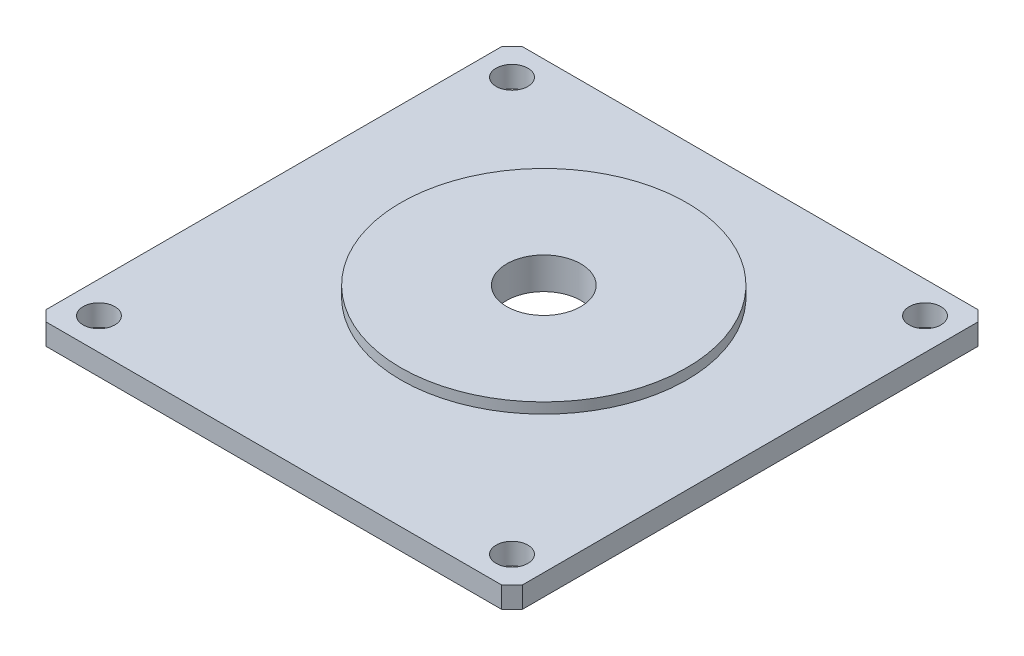
SolidWorks part; units mm, degrees
ref_plane "前视基准面" through (0, 0, 0) normal (0, 0, 1) x (1, 0, 0)
ref_plane "上视基准面" through (0, 0, 0) normal (0, 1, 0) x (1, 0, 0)
ref_plane "右视基准面" through (0, 0, 0) normal (1, 0, 0) x (0, 0, -1)
sketch "草图1" plane through (0, 0, 0) normal (0, 1, 0) x (1, 0, 0)
  line L1 (-22.5, -22.5) -> (22.5, -22.5)
  line L2 (-22.5, -22.5) -> (-22.5, 22.5)
  line L3 (-22.5, 22.5) -> (22.5, 22.5)
  line L4 (22.5, -22.5) -> (22.5, 22.5)
  line L5 (-22.5, -22.5) -> (22.5, 22.5) construction
  line L6 (-22.5, 22.5) -> (22.5, -22.5) construction
  point P0 (0, 0)
  dimension "D1" = 45
  dimension "D2" = 45
extrude "凸台-拉伸1" add sketch "草图1" along normal blind 2
sketch "草图2" plane through (0, 2, 0) normal (0, 1, 0) x (1, 0, 0)
  line L0 (0, 0) -> (0, 3) construction
  circle A0 centre (0, 3) radius 3.5
  dimension "D2" = 7
  dimension "D1" = 3
extrude "切除-拉伸1" cut sketch "草图2" against normal through all
sketch "草图3" plane through (0, 2, 0) normal (0, 1, 0) x (1, 0, 0)
  circle A0 centre (0, 3) radius 13.5
  circle A1 centre (0, 3) radius 3.5 construction
  circle A2 centre (0, 3) radius 3.5
  dimension "D1" = 27
extrude "凸台-拉伸2" add sketch "草图3" along normal blind 1
sketch "草图4" plane through (0, 0, 0) normal (0, 1, 0) x (1, 0, 0)
  line L0 (0, 22.5) -> (0, -22.5) construction
  line L1 (22.5, 22.5) -> (-22.5, 22.5) construction
  line L2 (-22.5, -22.5) -> (22.5, -22.5) construction
  line L3 (22.5, 0) -> (-22.5, 0) construction
  line L4 (22.5, -22.5) -> (22.5, 22.5) construction
  line L5 (-22.5, 22.5) -> (-22.5, -22.5) construction
  line L6 (22.5, 22.5) -> (-22.5, 22.5) construction
  circle A0 centre (19.5, 19.5) radius 1.5
  circle A1 centre (-19.5, 19.5) radius 1.5
  circle A2 centre (-19.5, -19.5) radius 1.5
  circle A3 centre (19.5, -19.5) radius 1.5
  dimension "D1" = 3
  dimension "D2" = 3
  dimension "D3" = 3
extrude "切除-拉伸4" cut sketch "草图4" along normal through all
chamfer "倒角1" distance 1 angle 45 4 edges at (-22.5, 1, 22.5) (22.5, 1, 22.5) (-22.5, 1, -22.5) (22.5, 1, -22.5)
